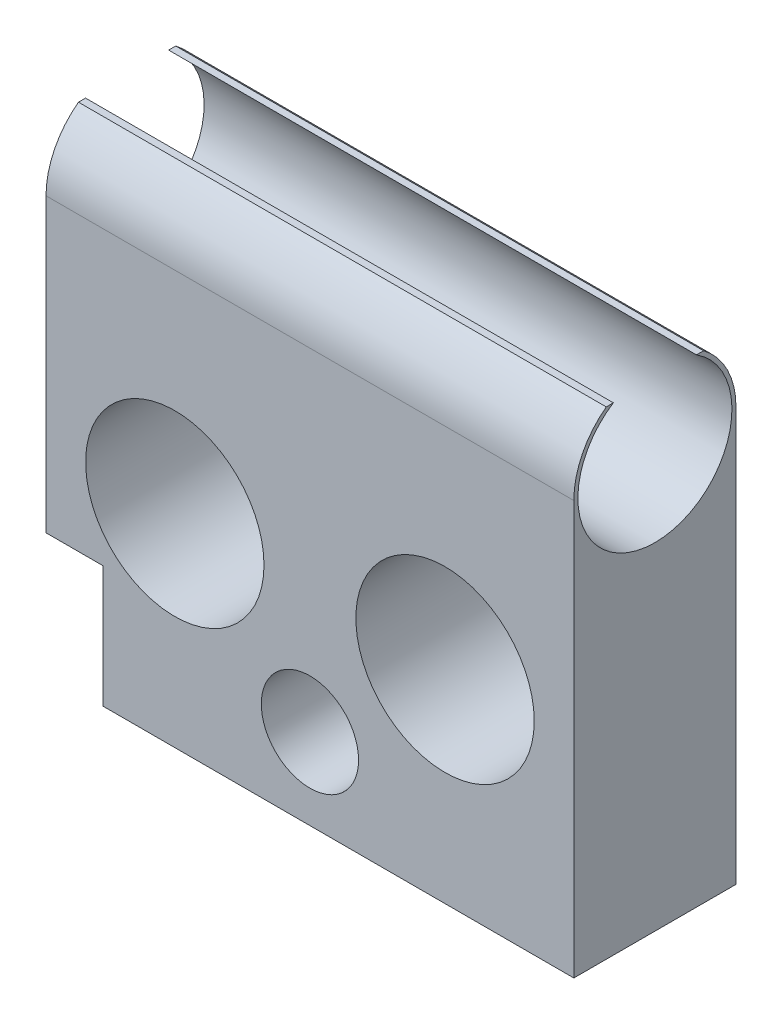
SolidWorks part; units mm, degrees
material "Manual Density from Real Component Plastica Fusoliera"
ref_plane "Piano frontale" through (0, 0, 0) normal (0, 0, 1) x (1, 0, 0)
ref_plane "Piano superiore" through (0, 0, 0) normal (0, 1, 0) x (1, 0, 0)
ref_plane "Piano destro" through (0, 0, 0) normal (1, 0, 0) x (0, 0, -1)
sketch "Schizzo1" plane through (0, 0, 0) normal (0, 0, 1) x (1, 0, 0)
  line L0 (-15.55, 0) -> (15.55, 0) construction
  line L2 (-30.55, 15) -> (30.55, 15) construction
  line L3 (-30.55, 15) -> (-30.55, -25) construction
  line L4 (-30.55, -25) -> (30.55, -25)
  line L5 (30.55, 15) -> (30.55, -25) construction
  line L6 (-30.55, -15) -> (30.55, -15) construction
  line L7 (-30.55, -25) -> (-32.55, -25)
  line L8 (-32.55, -25) -> (-32.55, 17)
  line L9 (-32.55, 17) -> (32.55, 17) construction
  line L10 (32.55, 17) -> (32.55, -25)
  line L11 (32.55, -25) -> (30.55, -25)
  line L13 (-32.55, 17) -> (32.55, 17) construction
  line L14 (-32.55, 17) -> (-32.55, 37)
  line L15 (-32.55, 37) -> (32.55, 37)
  line L16 (32.55, 17) -> (32.55, 37)
  circle A0 centre (-15.55, 0) radius 15 construction
  circle A1 centre (15.55, 0) radius 15 construction
  point P5 (0, 0)
  dimension "D2" = 30
  dimension "D1" = 31.1
  dimension "D3" = 10
  dimension "D4" = 2
  dimension "D5" = 2
  dimension "D6" = 2
  dimension "D7" = 20
extrude "ParallelepipedoBlocco" add sketch "Schizzo1" along normal blind 20
sketch "Schizzo2" plane through (0, 0, 20) normal (0, 0, 1) x (1, 0, 0)
  line L0 (-16.665, 0) -> (16.665, 0) construction
  line L3 (-32.55, 15) -> (32.55, 15) construction
  line L4 (-32.55, 37) -> (-32.55, -25) construction
  line L5 (32.55, -25) -> (32.55, 37) construction
  line L7 (-30.55, 17) -> (-30.55, -25) construction
  line L8 (-32.55, -25) -> (32.55, -25) construction
  line L9 (32.55, 17) -> (-32.55, 17) construction
  line L10 (32.55, -25) -> (32.55, 37) construction
  line L11 (-32.55, 37) -> (-32.55, -25) construction
  circle A0 centre (-16.665, 0) radius 11
  circle A1 centre (16.665, 0) radius 11
  circle A2 centre (0, -15) radius 6
  point P4 (0, 0)
  dimension "D5" = 22
  dimension "D6" = 12
  dimension "D1" = 2
  dimension "D2" = 2
  dimension "D3" = 20
  dimension "D4" = 33.33
  dimension "D7" = 15
extrude "ForiTubiMotori" cut sketch "Schizzo2" against normal through all
sketch "Schizzo4" plane through (-32.55, 0, 0) normal (-1, 0, 0) x (0, 0, 1)
  line L0 (20, 37) -> (0, 37) construction
  circle A0 centre (10, 26) radius 9.5
  point P6 (10, 37)
  dimension "D1" = 19
  dimension "D2" = 11
extrude "ForoLongherone" cut sketch "Schizzo4" against normal through all
sketch "Schizzo5" plane through (-32.55, 0, 0) normal (-1, 0, 0) x (0, 0, 1)
  line L0 (20, 37) -> (20, -25) construction
  line L1 (0, 26) -> (0, 37)
  line L2 (0, -34.1) -> (0, 34.1) construction
  line L3 (0, 37) -> (20, 37)
  line L4 (20, 37) -> (20, 26)
  arc A0 (20, 26) -> (0, 26) centre (10, 26) ccw
extrude "EliminazioneParteSuperiore" cut sketch "Schizzo5" against normal through all
ref_plane "PianoMezzeriaLongherone" through (0, 0, 10) normal (0, 0, 1) x (1, 0, 0)
sketch "Schizzo6" plane through (0, 0, 20) normal (0, 0, 1) x (1, 0, 0)
  line L1 (-32.55, -25) -> (-25.5, -25)
  line L2 (-32.55, -25) -> (-32.55, -10)
  line L3 (-32.55, -10) -> (-25.5, -10)
  line L4 (-25.5, -25) -> (-25.5, -10)
  dimension "D1" = 7.05
  dimension "D2" = 15
extrude "SpazioMovimentoLevetta" cut sketch "Schizzo6" against normal through all
sketch "Schizzo7" plane through (-32.55, 0, 0) normal (-1, 0, 0) x (0, 0, 1)
  line L0 (0, -33.55) -> (0, 33.55) construction
  line L1 (20, 36) -> (0, 36)
  line L2 (20, 36) -> (20, 34)
  line L3 (20, 34) -> (0, 34)
  line L4 (0, 36) -> (0, 34)
  line L5 (20, 26) -> (20, -10) construction
  arc A0 (20, 26) -> (0, 26) centre (10, 26) ccw construction
  dimension "D1" = 2
extrude "RimozioneParteSuperiore" cut sketch "Schizzo7" against normal up to surface (65.1 mm away) up to face at (32.55, 26, 19.5)
